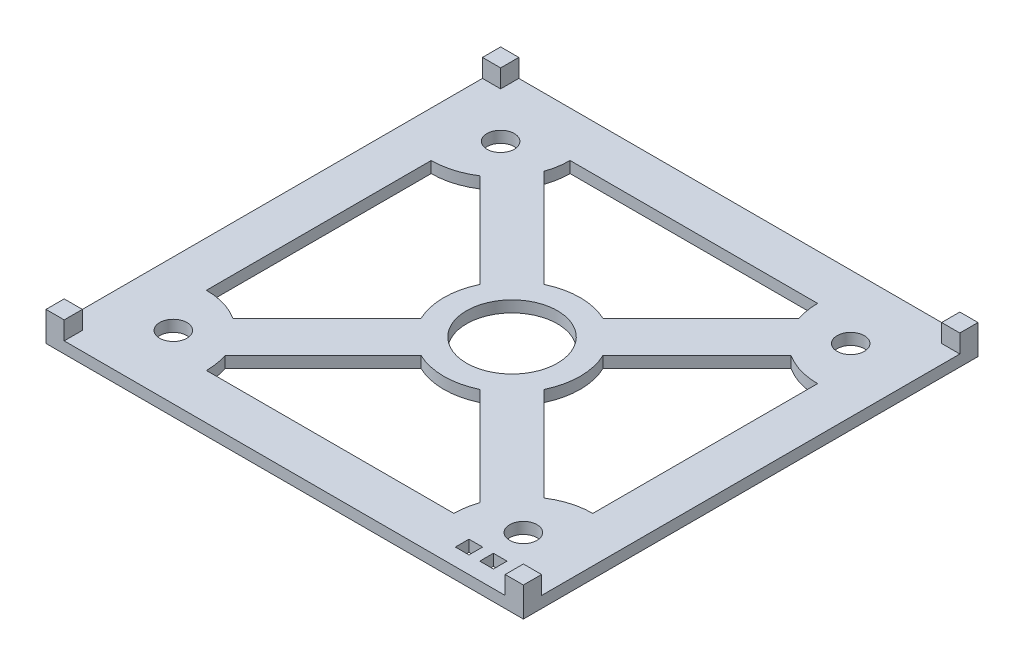
SolidWorks part; units mm, degrees
ref_plane "Front Plane" through (0, 0, 0) normal (0, 0, 1) x (1, 0, 0)
ref_plane "Top Plane" through (0, 0, 0) normal (0, 1, 0) x (1, 0, 0)
ref_plane "Right Plane" through (0, 0, 0) normal (1, 0, 0) x (0, 0, -1)
sketch "Sketch1" plane through (0, 0, 0) normal (0, 1, 0) x (1, 0, 0)
  line L1 (-52.5, -50) -> (52.5, -50)
  line L2 (-52.5, -50) -> (-52.5, 50)
  line L3 (-52.5, 50) -> (52.5, 50)
  line L4 (52.5, -50) -> (52.5, 50)
  line L5 (-52.5, -50) -> (52.5, 50) construction
  line L6 (-52.5, 50) -> (52.5, -50) construction
  point P0 (0, 0)
  dimension "D1" = 105
  dimension "D2" = 100
extrude "Boss-Extrude1" add sketch "Sketch1" along normal blind 2.5
sketch "Sketch3" plane through (0, 2.5, 0) normal (0, 1, 0) x (1, 0, 0)
  line L0 (-69.1295, 0) -> (69.1295, 0)
  line L1 (-52.5, 50) -> (-48.5, 50)
  line L2 (-52.5, 50) -> (-52.5, 46)
  line L3 (-52.5, 46) -> (-48.5, 46)
  line L4 (-48.5, 50) -> (-48.5, 46)
  line L5 (52.5, -50) -> (48.5, -50)
  line L6 (52.5, 50) -> (48.5, 50)
  line L7 (52.5, 50) -> (52.5, 46)
  line L8 (52.5, 46) -> (48.5, 46)
  line L9 (48.5, 50) -> (48.5, 46)
  line L10 (52.5, -50) -> (52.5, -46)
  line L11 (52.5, -46) -> (48.5, -46)
  line L12 (48.5, -50) -> (48.5, -46)
  line L13 (-48.5, -50) -> (-48.5, -46)
  line L14 (-52.5, -50) -> (-48.5, -50)
  line L15 (-52.5, -50) -> (-52.5, -46)
  line L16 (-52.5, -46) -> (-48.5, -46)
  point P9 (0, 0)
  line M14 (52.5, -50) -> (52.5, 50)
  line M15 (52.5, 50) -> (-52.5, 50)
  line M16 (-52.5, 50) -> (-52.5, -50)
  line M17 (-52.5, -50) -> (52.5, -50)
  dimension "D1" = 4
extrude "Boss-Extrude2" add sketch "Sketch3" along normal blind 4 contours L4 L3 M15 M16 | L9 L8 M15 M14 | L12 L11 M17 M14 | L16 L13 M16 M17
sketch "Sketch4" plane through (0, 2.5, 0) normal (0, 1, 0) x (1, 0, 0)
sketch "Sketch5" plane through (0, 2.5, 0) normal (0, 1, 0) x (1, 0, 0)
  line L1 (-42.5, -40) -> (42.5, -40)
  line L2 (-42.5, -40) -> (-42.5, 40)
  line L3 (-42.5, 40) -> (42.5, 40)
  line L4 (42.5, -40) -> (42.5, 40)
  line L5 (-42.5, -40) -> (42.5, 40) construction
  line L6 (-42.5, 40) -> (42.5, -40) construction
  line L7 (52.5, -46) -> (52.5, 46) construction
  line L8 (-48.5, -50) -> (48.5, -50) construction
  point P0 (0, 0)
  dimension "D1" = 10
  dimension "D2" = 10
extrude "Cut-Extrude2" cut sketch "Sketch5" against normal blind 4
sketch "Sketch6" plane through (0, 2.5, 0) normal (0, 1, 0) x (1, 0, 0)
  circle A0 centre (0, 0) radius 15
  dimension "D1" = 30
extrude "Boss-Extrude3" add sketch "Sketch6" against normal blind 2.5 separate body
sketch "Sketch7" plane through (0, 2.5, 0) normal (0, 1, 0) x (1, 0, 0)
  line L1 (-2.5, -2.5) -> (2.5, -2.5)
  line L2 (-2.5, -2.5) -> (-2.5, 2.5)
  line L3 (-2.5, 2.5) -> (2.5, 2.5)
  line L4 (2.5, -2.5) -> (2.5, 2.5)
  line L5 (-2.5, -2.5) -> (2.5, 2.5) construction
  line L6 (-2.5, 2.5) -> (2.5, -2.5) construction
  point P0 (0, 0)
  dimension "D1" = 5
  dimension "D2" = 5
extrude "Cut-Extrude3" cut sketch "Sketch7" against normal blind 2.5
sketch "Sketch8" plane through (0, 2.5, 0) normal (0, 1, 0) x (1, 0, 0)
  line L0 (42.5, -40) -> (42.5, 40) construction
  line L1 (42.5, 40) -> (-42.5, 40) construction
  line L2 (0, -54.2426) -> (0, 54.2426)
  line L3 (27.2201, 40) -> (42.5, 40)
  line L4 (42.5, 40) -> (42.5, 24.7201)
  line L5 (-63.2717, 0) -> (63.2717, 0)
  arc A0 (42.5, 24.7201) -> (27.2201, 40) centre (42.5, 40) cw
  arc A1 (-42.5, 24.7201) -> (-27.2201, 40) centre (-42.5, 40) ccw
  arc A2 (42.5, -24.7201) -> (27.2201, -40) centre (42.5, -40) ccw
  arc A3 (-42.5, -24.7201) -> (-27.2201, -40) centre (-42.5, -40) cw
  point P13 (0, 0)
  point P15 (0, 0)
  line M3 (-42.5, 40) -> (42.5, 40)
  line M4 (42.5, 40) -> (42.5, -40)
  line M5 (42.5, -40) -> (-42.5, -40)
  line M6 (-42.5, -40) -> (-42.5, 40)
extrude "Boss-Extrude4" add sketch "Sketch8" against normal blind 2.5 contours A3 M6 M5 | A1 M6 M3 | A0 M4 M3 | A2 M4 M5
sketch "Sketch9" plane through (0, 2.5, 0) normal (0, 1, 0) x (1, 0, 0)
  line L0 (2.5, -2.5) -> (38.0042, -38.0042)
  line L2 (-7.75, -7.75) -> (-38.0042, -38.0042)
  line L4 (7.75, 7.75) -> (38.0042, 38.0042)
  line L5 (-7.75, 7.75) -> (-38.0042, 38.0042)
  point P17 (0, 0)
  point P22 (0, 0)
extrude "Extrude-Thin2" add sketch "Sketch9" against normal blind 2.5 thin thin type mid plane wall 10
sketch "Sketch10" plane through (0, 2.5, 0) normal (0, 1, 0) x (1, 0, 0)
  line L0 (48.5, 50) -> (-48.5, 50) construction
  line L1 (52.5, -46) -> (52.5, 46) construction
  line L2 (-81.3718, 0) -> (93.495, 0) construction
  line L3 (0, 82.8678) -> (0, -87.0228) construction
  circle A0 centre (38.5, 36) radius 3
  circle A1 centre (-38.5, 36) radius 3
  circle A2 centre (38.5, -36) radius 3
  circle A3 centre (-38.5, -36) radius 3
  dimension "D1" = 6
  dimension "D2" = 14
  dimension "D3" = 14
extrude "Cut-Extrude5" cut sketch "Sketch10" against normal blind 2.5
sketch "Sketch11" plane through (0, 2.5, 0) normal (0, 1, 0) x (1, 0, 0)
  line L0 (37.9743, -39.1284) -> (37.9743, -49.44) construction
  line L1 (39.1573, -46.2521) -> (42.1573, -46.2521)
  line L2 (39.1573, -46.2521) -> (39.1573, -43.2521)
  line L3 (39.1573, -43.2521) -> (42.1573, -43.2521)
  line L4 (42.1573, -46.2521) -> (42.1573, -43.2521)
  line L5 (39.1573, -46.2521) -> (42.1573, -43.2521) construction
  line L6 (39.1573, -43.2521) -> (42.1573, -46.2521) construction
  line L7 (36.7914, -43.2521) -> (33.7914, -46.2521) construction
  line L8 (36.7914, -46.2521) -> (33.7914, -43.2521) construction
  line L9 (33.7914, -46.2521) -> (33.7914, -43.2521)
  line L10 (36.7914, -43.2521) -> (33.7914, -43.2521)
  line L11 (36.7914, -46.2521) -> (36.7914, -43.2521)
  line L12 (36.7914, -46.2521) -> (33.7914, -46.2521)
  point P0 (40.6573, -44.7521)
  point P11 (35.2914, -44.7521)
  dimension "D1" = 3
  dimension "D2" = 3
extrude "Cut-Extrude6" cut sketch "Sketch11" against normal blind 2.5
sketch "Sketch12" plane through (0, 2.5, 0) normal (0, 1, 0) x (1, 0, 0)
  circle A0 centre (0, 0) radius 10
  dimension "D1" = 20
extrude "Cut-Extrude7" cut sketch "Sketch12" against normal blind 10
